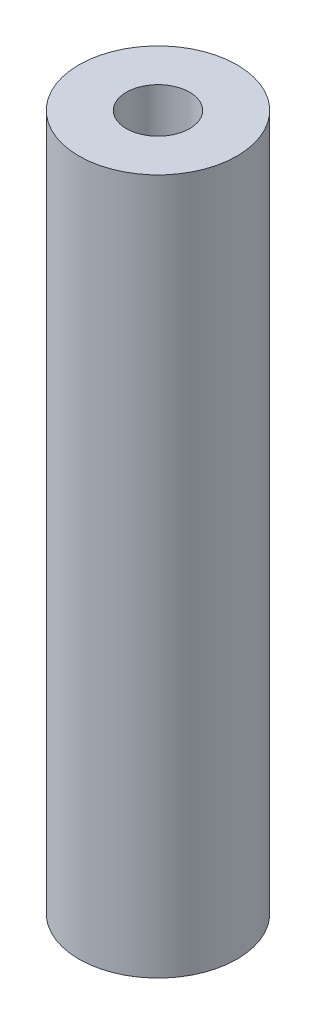
SolidWorks part; units mm, degrees
ref_plane "Front Plane" through (0, 0, 0) normal (0, 0, 1) x (1, 0, 0)
ref_plane "Top Plane" through (0, 0, 0) normal (0, 1, 0) x (1, 0, 0)
ref_plane "Right Plane" through (0, 0, 0) normal (1, 0, 0) x (0, 0, -1)
sketch "Sketch1" plane through (0, 0, 0) normal (0, 1, 0) x (1, 0, 0)
  circle A0 centre (0, 0) radius 2.5
  circle A1 centre (0, 0) radius 1
  dimension "D1" = 5
  dimension "D2" = 2
extrude "Boss-Extrude1" add sketch "Sketch1" along normal blind 22
